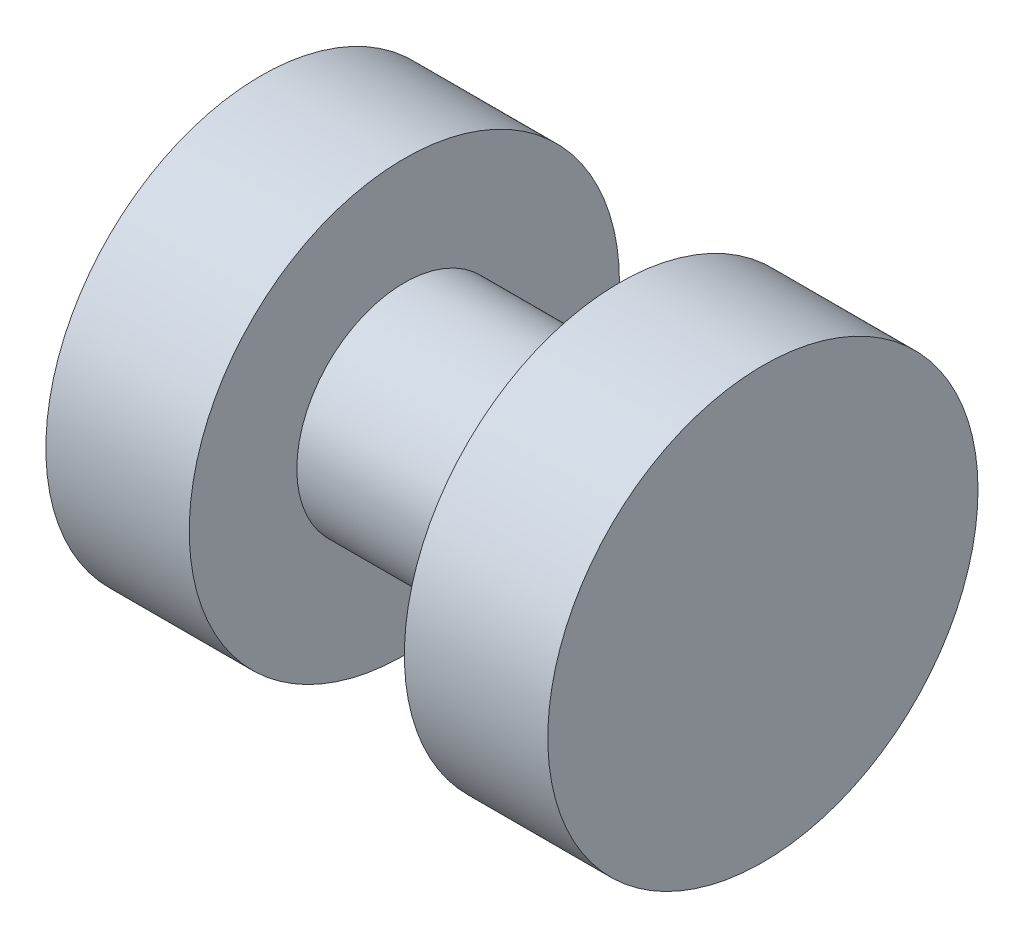
SolidWorks part; units mm, degrees
material "Plain Carbon Steel"
ref_plane "Front Plane" through (0, 0, 0) normal (0, 0, 1) x (1, 0, 0)
ref_plane "Top Plane" through (0, 0, 0) normal (0, 1, 0) x (1, 0, 0)
ref_plane "Right Plane" through (0, 0, 0) normal (1, 0, 0) x (0, 0, -1)
sketch "Sketch1" plane through (0, 0, 0) normal (1, 0, 0) x (0, 0, -1)
  circle A0 centre (0, 0) radius 3
  dimension "D1" = 6
extrude "Boss-Extrude1" add sketch "Sketch1" along normal blind 2
sketch "Sketch2" plane through (2, 0, 0) normal (1, 0, 0) x (0, 0, -1)
  circle A0 centre (0, 0) radius 1.5
  dimension "D1" = 3
extrude "Boss-Extrude2" add sketch "Sketch2" along normal blind 3
sketch "Sketch3" plane through (5, 0, 0) normal (1, 0, 0) x (0, 0, -1)
  circle A0 centre (0, 0) radius 3
  dimension "D1" = 6
extrude "Boss-Extrude3" add sketch "Sketch3" along normal blind 2
